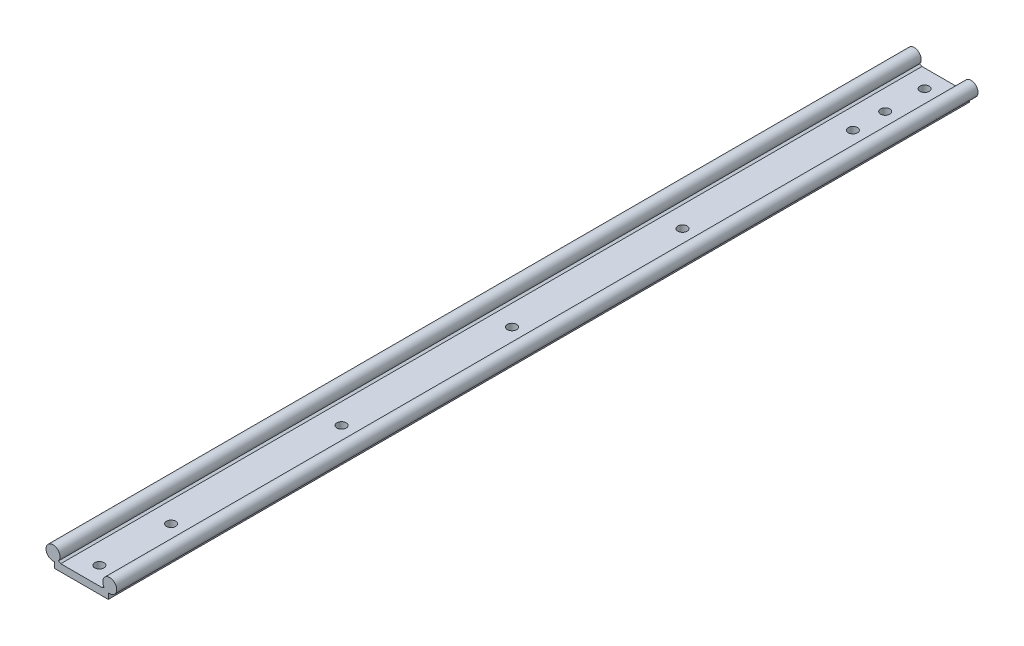
SolidWorks part; units mm, degrees
material "AISI 316 Annealed Stainless Steel Bar (SS)"
ref_plane "Front Plane" through (0, 0, 0) normal (0, 0, 1) x (1, 0, 0)
ref_plane "Top Plane" through (0, 0, 0) normal (0, 1, 0) x (1, 0, 0)
ref_plane "Right Plane" through (0, 0, 0) normal (1, 0, 0) x (0, 0, -1)
sketch "Sketch1" plane through (0, 0, 0) normal (0, 0, 1) x (1, 0, 0)
  line L0 (-14.605, 5.08) -> (14.605, 5.08)
  line L2 (-19.05, 4.1747) -> (-19.05, 0)
  line L3 (-19.05, 0) -> (19.05, 0)
  line L4 (19.05, 4.1747) -> (19.05, 0)
  line L5 (-14.605, 5.08) -> (-16.1741, 5.9859)
  line L6 (14.605, 5.08) -> (16.1741, 5.9859)
  arc A0 (-16.1741, 5.9859) -> (-19.05, 4.1747) centre (-20.0914, 9.017) ccw
  arc A1 (19.05, 4.1747) -> (16.1741, 5.9859) centre (20.0914, 9.017) ccw
  point P4 (0, 0)
  dimension "D3" = 9.906
  dimension "D4" = 50.0888
  dimension "D5" = 25.0444
  dimension "D6" = 13.97
  dimension "D1" = 38.1
  dimension "D2" = 30
  dimension "D7" = 5.08
  dimension "D8" = 30
  dimension "D9" = 29.21
  dimension "D10" = 14.605
extrude "Boss-Extrude1" add sketch "Sketch1" along normal mid plane 609.6
sketch "Sketch2" plane through (0, 5.08, 0) normal (0, 1, 0) x (1, 0, 0)
  line L0 (14.605, -304.8) -> (-14.605, -304.8) construction
  circle A0 centre (0, -292.1) radius 3.2766
  dimension "D1" = 12.7
extrude "Cut-Extrude2" cut sketch "Sketch2" against normal through all
sketch "Sketch4" plane through (0, 5.08, 0) normal (0, 1, 0) x (1, 0, 0)
  line L0 (14.605, -304.8) -> (-14.605, -304.8) construction
  circle A0 centre (0, -241.3) radius 3.2766
  circle A1 centre (0, -120.65) radius 3.2766
  circle A2 centre (0, 0) radius 3.2766
  circle A3 centre (0, 120.65) radius 3.2766
  circle A4 centre (0, 241.3) radius 3.2766
  dimension "D1" = 63.5
  dimension "D2" = 5
extrude "Cut-Extrude4" cut sketch "Sketch4" against normal blind 25.4
sketch "Sketch5" plane through (0, 5.08, 0) normal (0, 1, 0) x (1, 0, 0)
  line L0 (14.605, 304.8) -> (-14.605, 304.8) construction
  circle A0 centre (0, 292.1) radius 3.2766
  dimension "D1" = 12.7
extrude "Cut-Extrude5" cut sketch "Sketch5" against normal blind 25.4
sketch "Sketch6" plane through (0, 5.08, 0) normal (0, 1, 0) x (1, 0, 0)
  circle A0 centre (0, 264.16) radius 3.2766
  circle A1 centre (0, 292.1) radius 3.2766 construction
  dimension "D1" = 27.94
extrude "Cut-Extrude8" cut sketch "Sketch6" against normal blind 25.4
